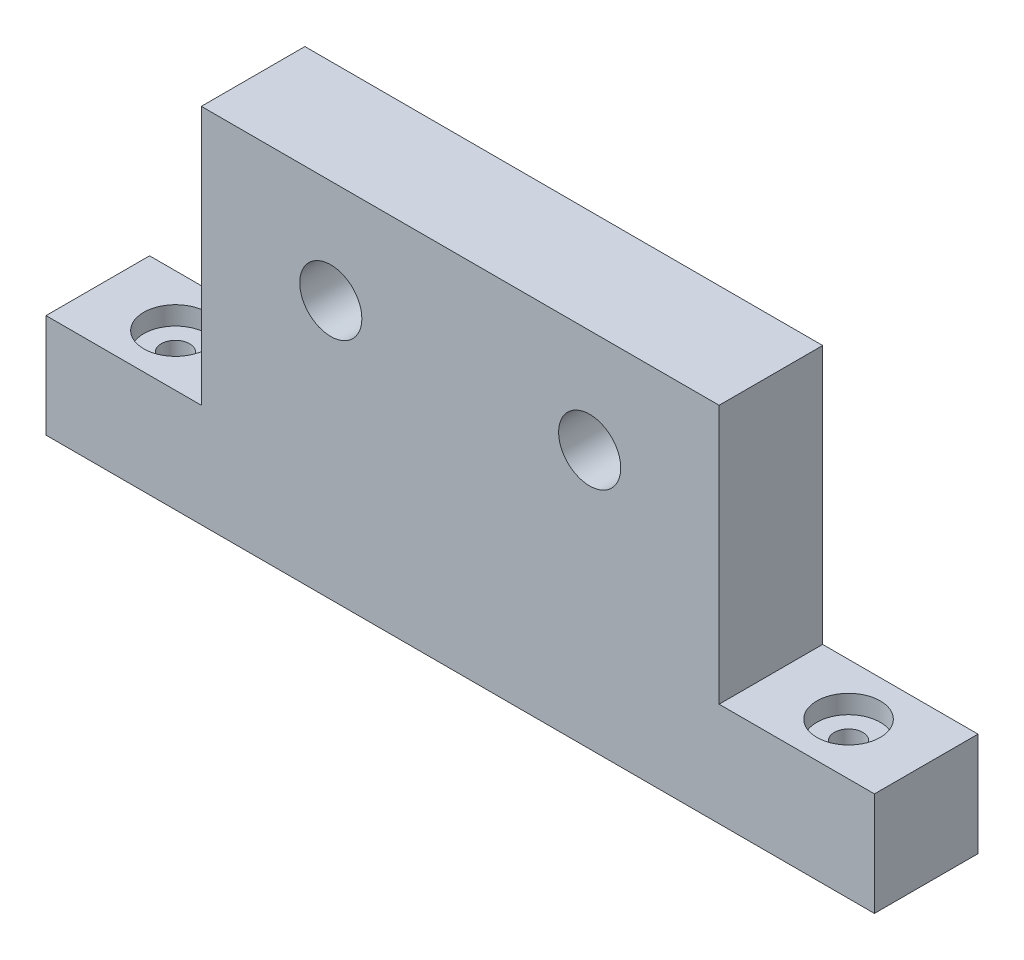
SolidWorks part; units mm, degrees
ref_plane "Front Plane" through (0, 0, 0) normal (0, 0, 1) x (1, 0, 0)
ref_plane "Top Plane" through (0, 0, 0) normal (0, 1, 0) x (1, 0, 0)
ref_plane "Right Plane" through (0, 0, 0) normal (1, 0, 0) x (0, 0, -1)
sketch "Sketch2" plane through (0, 0, 0) normal (0, 0, 1) x (1, 0, 0)
  line L0 (0, 0) -> (0, 70) construction
  line L1 (80, 0) -> (-80, 0)
  line L2 (-80, 0) -> (-80, 20)
  line L3 (-80, 20) -> (-50, 20)
  line L4 (-50, 20) -> (-50, 70)
  line L5 (-50, 70) -> (0, 70)
  line L10 (50, 70) -> (0, 70)
  line L11 (50, 20) -> (50, 70)
  line L12 (80, 20) -> (50, 20)
  line L13 (80, 0) -> (80, 20)
  circle A0 centre (-25, 50) radius 6
  circle A1 centre (25, 50) radius 6
  dimension "D5" = 12
  dimension "D7" = 50
  dimension "D6" = 50
  dimension "D1" = 70
  dimension "D2" = 80
  dimension "D3" = 30
  dimension "D4" = 20
extrude "Corpo - Furos 12mm" add sketch "Sketch2" along normal blind 20
hole_wizard "Furos Ø6mm" positions "Sketch4" profile "Sketch5" counterbore size "M5" standard "ANSI Metric" end condition through all
sketch "Sketch4" plane through (0, 20, 0) normal (0, 1, 0) x (1, 0, 0)
  line L0 (-65, -10) -> (65, -10) construction
  line L2 (-50, -20) -> (-80, -20) construction
  line L3 (-80, -20) -> (-80, 0) construction
  point P0 (-65, -10)
  point P2 (65, -10)
  dimension "D1" = 10
  dimension "D2" = 15
  dimension "D3" = 130
sketch "Sketch5" plane through (-65, 20, 10) normal (1, 0, 0) x (0, 0, 1)
  line L0 (0, 0) -> (0, 20)
  line L1 (0, 20) -> (2.75, 20)
  line L3 (2.75, 20) -> (2.75, 3.58)
  line L4 (2.75, 3.58) -> (6.12, 3.58)
  line L5 (6.12, 3.58) -> (6.12, 0)
  line L7 (6.12, 0) -> (0, 0)
  line L11 (0, -6.35) -> (0, 107.95) construction
  dimension "Thru Hole Dia." = 5.5
  dimension "Thru Hole Depth" = 20
  dimension "C'Bore Dia." = 12.24
  dimension "C'Bore Depth" = 3.58
